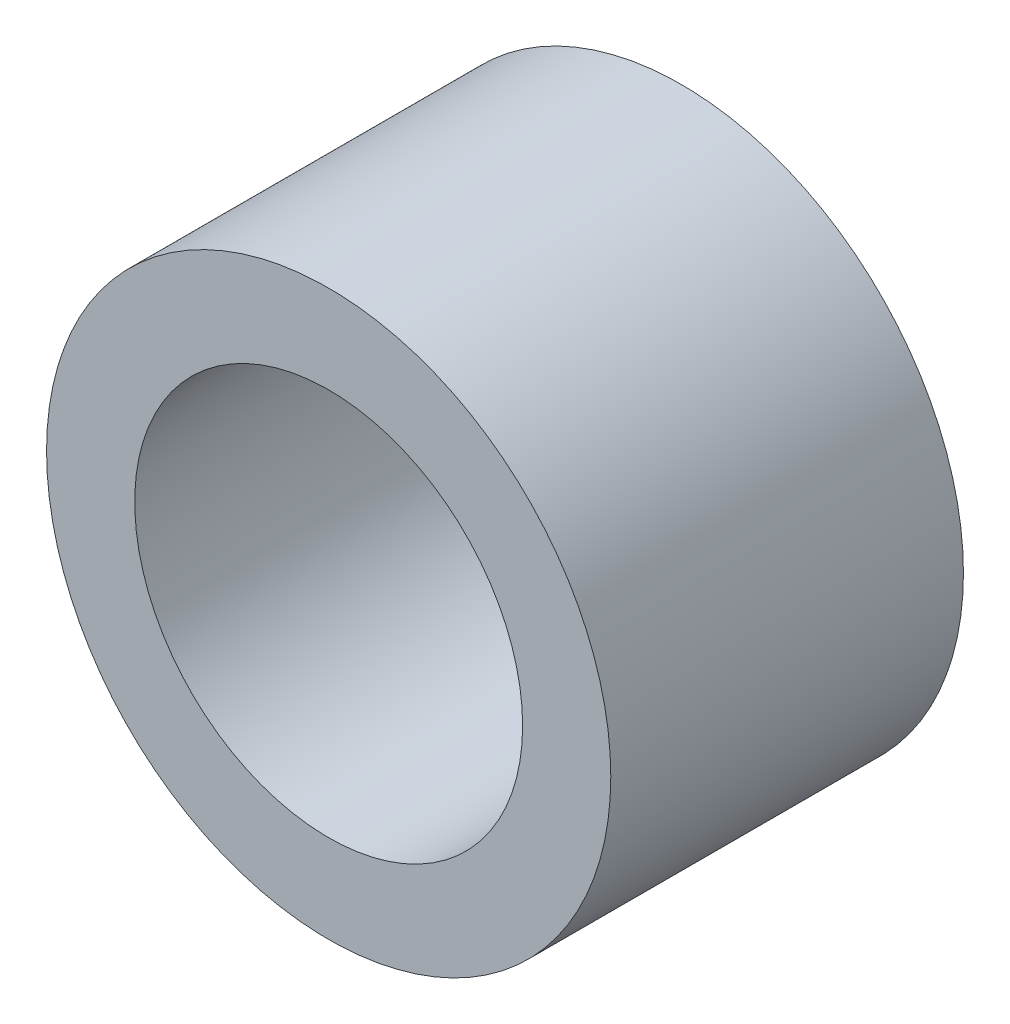
SolidWorks part; units mm, degrees
ref_plane "Front Plane" through (0, 0, 0) normal (0, 0, 1) x (1, 0, 0)
ref_plane "Top Plane" through (0, 0, 0) normal (0, 1, 0) x (1, 0, 0)
ref_plane "Right Plane" through (0, 0, 0) normal (1, 0, 0) x (0, 0, -1)
sketch "Sketch1" plane through (0, 0, 0) normal (0, 0, 1) x (1, 0, 0)
  circle A0 centre (0, 0) radius 4
  dimension "D1" = 8
extrude "Boss-Extrude1" add sketch "Sketch1" along normal blind 5
hole_wizard "M5 Clearance Hole1" positions "Sketch2" profile "Sketch3" hole size "M5" standard "ANSI Metric"
sketch "Sketch2" plane through (0, 0, 5) normal (0, 0, 1) x (1, 0, 0)
  point P0 (0, 0)
sketch "Sketch3" plane through (0, 0, 5) normal (1, 0, 0) x (0, -1, 0)
  line L0 (0, 0) -> (0, 11.6524)
  line L1 (0, 11.6524) -> (2.75, 10)
  line L2 (2.75, 10) -> (2.75, 0)
  line L5 (2.75, 0) -> (0, 0)
  line L10 (0, 11.6524) -> (-2.75, 10) construction
  line L11 (0, -6.35) -> (0, 107.95) construction
  dimension "Hole Dia." = 5.5
  dimension "Hole Depth" = 10
  dimension "Drill Angle" = 118
